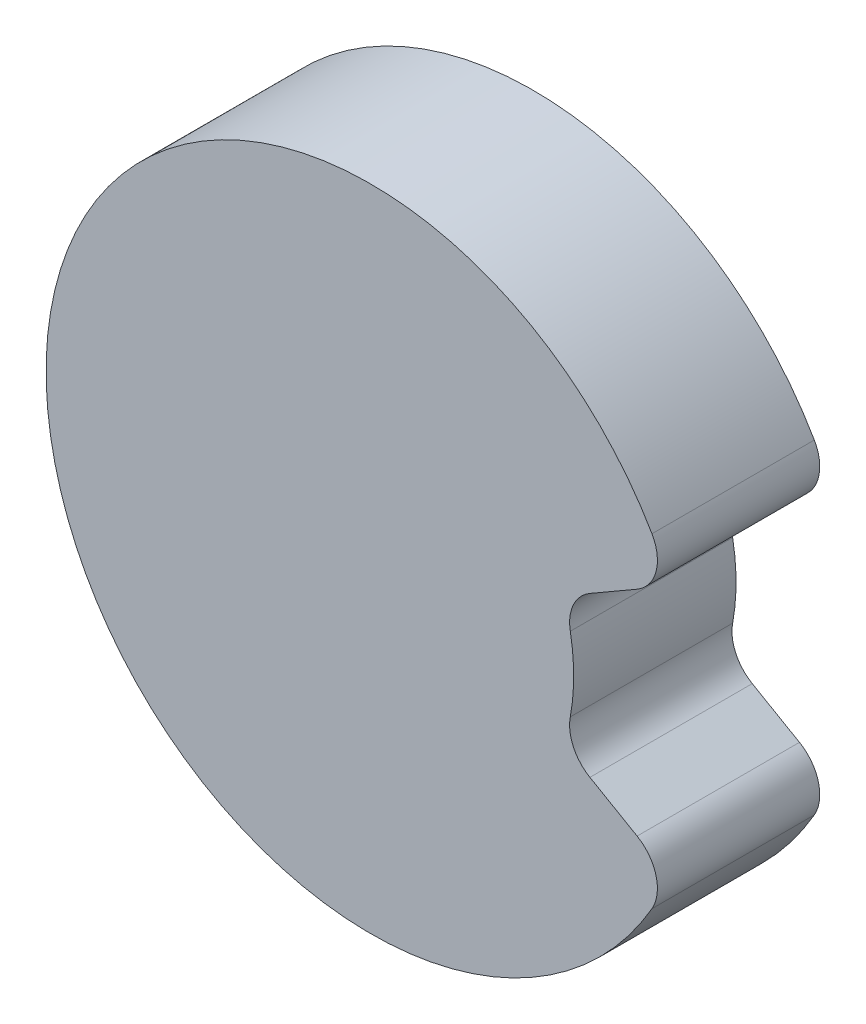
SolidWorks part; units mm, degrees
material "EPS Foam"
ref_plane "Front Plane" through (0, 0, 0) normal (1, 0, 0) x (0, 1, 0)
ref_plane "Top Plane" through (0, 0, 0) normal (0, 0, 1) x (0, 1, 0)
ref_plane "Right Plane" through (0, 0, 0) normal (0, 1, 0) x (-1, 0, 0)
sketch "Sketch1" plane through (0, 0, 0) normal (0, 0, 1) x (0, 1, 0)
  line L0 (0, 0) -> (-50.8, -87.9882) construction
  line L1 (0, 0) -> (0, -101.6) construction
  line L2 (0, 0) -> (50.8, -87.9882) construction
  line L3 (-39.403, -93.6481) -> (-20.11, -60.2315)
  line L4 (39.403, -93.6481) -> (20.11, -60.2315)
  arc A0 (39.403, -93.6481) -> (-39.403, -93.6481) centre (0, 0) ccw
  arc A1 (-20.11, -60.2315) -> (20.11, -60.2315) centre (0, 0) ccw
  dimension "D2" = 203.2
  dimension "D4" = 63.5
  dimension "D1" = 60
  dimension "D3" = 12.7
extrude "Boss-Extrude1" add sketch "Sketch1" along normal mid plane 50.8
fillet "Fillet1" radius 12.7 4 edges at (93.6481, 39.403, 0) (60.2315, 20.11, 0) (93.6481, -39.403, 0) (60.2315, -20.11, 0)
sketch "Sketch2" [suppressed] plane through (0, 0, 25.4) normal (0, 0, 1) x (1, 0, 0)
  line L0 (67.297, 27.1222) -> (82.0697, 35.6512)
  line L1 (82.0697, -35.6512) -> (67.297, -27.1222)
  line L2 (68.567, 24.9225) -> (83.3397, 33.4515)
  line L3 (83.3397, -33.4515) -> (68.567, -24.9225)
  line L4 (68.567, 24.9225) -> (83.3397, 33.4515)
  line L5 (83.3397, -33.4515) -> (68.567, -24.9225)
  arc A0 (82.0697, 35.6512) -> (85.7885, 49.53) centre (76.9897, 44.45) ccw
  arc A1 (85.7885, 49.53) -> (85.7885, -49.53) centre (0, 0) ccw
  arc A2 (85.7885, -49.53) -> (82.0697, -35.6512) centre (76.9897, -44.45) ccw
  arc A3 (59.9336, -11.1392) -> (67.297, -27.1222) centre (74.917, -13.924) ccw
  arc A4 (59.9336, -11.1392) -> (59.9336, 11.1392) centre (0, 0) ccw
  arc A5 (67.297, 27.1222) -> (59.9336, 11.1392) centre (74.917, 13.924) ccw
  arc A6 (83.3397, 33.4515) -> (87.9882, 50.8) centre (76.9897, 44.45) ccw
  arc A7 (87.9882, 50.8) -> (87.9882, -50.8) centre (0, 0) ccw
  arc A8 (87.9882, -50.8) -> (83.3397, -33.4515) centre (76.9897, -44.45) ccw
  arc A9 (62.4309, -11.6033) -> (68.567, -24.9225) centre (74.917, -13.924) ccw
  arc A10 (62.4309, -11.6033) -> (62.4309, 11.6033) centre (0, 0) ccw
  arc A11 (68.567, 24.9225) -> (62.4309, 11.6033) centre (74.917, 13.924) ccw
  arc A12 (83.3397, 33.4515) -> (87.9882, 50.8) centre (76.9897, 44.45) ccw
  arc A13 (87.9882, 50.8) -> (87.9882, -50.8) centre (0, 0) ccw
  arc A14 (87.9882, -50.8) -> (83.3397, -33.4515) centre (76.9897, -44.45) ccw
  arc A15 (62.4309, -11.6033) -> (68.567, -24.9225) centre (74.917, -13.924) ccw
  arc A16 (62.4309, -11.6033) -> (62.4309, 11.6033) centre (0, 0) ccw
  arc A17 (68.567, 24.9225) -> (62.4309, 11.6033) centre (74.917, 13.924) ccw
  dimension "D1" = 0
  dimension "D2" = 2.54
extrude "Boss-Extrude2" [suppressed] add sketch "Sketch2" along normal blind 3.175 separate body
delete or keep bodies "Body-Delete/Keep 1" [suppressed] type delete bodies bodies 101
sketch "Sketch3" [suppressed] plane through (0, 0, 28.575) normal (0, 0, 1) x (1, 0, 0)
  line L0 (-99.06, 0) -> (-44.45, 0)
  line L1 (0, -99.06) -> (0, -44.45)
  line L2 (-70.046, 70.046) -> (-31.4309, 31.4309)
  line L3 (-70.046, -70.046) -> (-31.4309, -31.4309)
  line L4 (31.4309, -31.4309) -> (70.046, -70.046)
  line L5 (0, 44.45) -> (0, 99.06)
  line L6 (31.4309, 31.4309) -> (70.046, 70.046)
  line L7 (44.45, 0) -> (60.96, 0)
  arc A1 (59.9336, -11.1392) -> (59.9336, 11.1392) centre (0, 0) ccw construction
  arc A2 (85.7885, 49.53) -> (85.7885, -49.53) centre (0, 0) ccw construction
  circle A3 centre (0, 0) radius 44.45
  dimension "D3" = 88.9
  dimension "D1" = 45
  dimension "D2" = 45
extrude "Extrude-Thin1" [suppressed] add sketch "Sketch3" against normal up to surface (3.175 mm away) thin
fillet "Fillet2" [suppressed] radius 2.54
